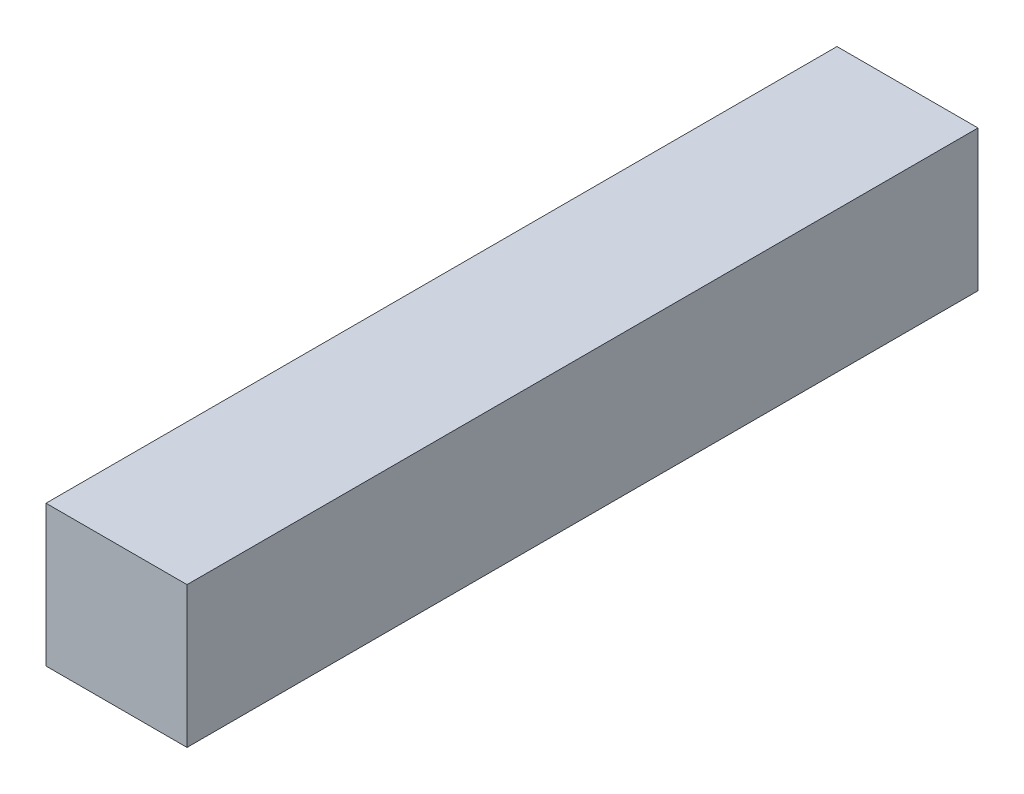
SolidWorks part; units mm, degrees
ref_plane "Front Plane" through (0, 0, 0) normal (0, 0, 1) x (1, 0, 0)
ref_plane "Top Plane" through (0, 0, 0) normal (0, 1, 0) x (1, 0, 0)
ref_plane "Right Plane" through (0, 0, 0) normal (1, 0, 0) x (0, 0, -1)
sketch "Sketch1" plane through (0, 0, 0) normal (0, 0, 1) x (1, 0, 0)
  line L0 (-31.8884, 0) -> (31.8884, 0) construction
  line L1 (0, -29.4643) -> (0, 29.4643) construction
  line L3 (-3.9624, -3.9624) -> (3.9624, -3.9624)
  line L4 (-3.9624, -3.9624) -> (-3.9624, 3.9624)
  line L5 (-3.9624, 3.9624) -> (3.9624, 3.9624)
  line L6 (3.9624, -3.9624) -> (3.9624, 3.9624)
  line L7 (-3.9624, -3.9624) -> (3.9624, 3.9624) construction
  line L8 (-3.9624, 3.9624) -> (3.9624, -3.9624) construction
  point P0 (0, 0)
  point P4 (0, 0)
  point P8 (0, 0)
  dimension "D1" = 7.9248
  dimension "D2" = 7.9248
extrude "Boss-Extrude1" add sketch "Sketch1" along normal mid plane 44.45
